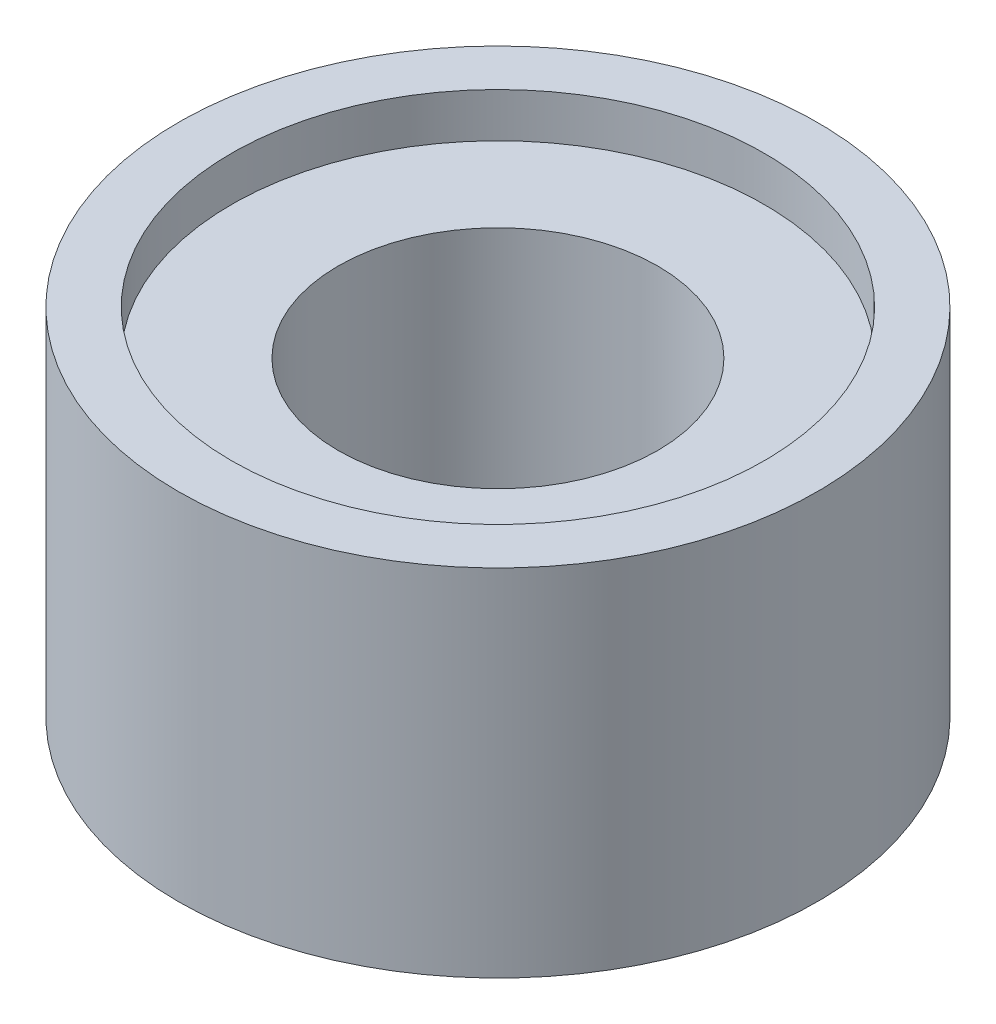
SolidWorks part; units mm, degrees
ref_plane "Front Plane" through (0, 0, 0) normal (0, 0, 1) x (1, 0, 0)
ref_plane "Top Plane" through (0, 0, 0) normal (0, 1, 0) x (1, 0, 0)
ref_plane "Right Plane" through (0, 0, 0) normal (1, 0, 0) x (0, 0, -1)
sketch "Sketch1" plane through (0, 0, 0) normal (0, 1, 0) x (1, 0, 0)
  circle A0 centre (0, 0) radius 9
  circle A1 centre (0, 0) radius 15
  dimension "D1" = 18
  dimension "D2" = 30
extrude "Boss-Extrude1" add sketch "Sketch1" along normal mid plane 15
sketch "Sketch3" plane through (0, 0, 0) normal (0, 1, 0) x (1, 0, 0)
  circle A0 centre (0, 0) radius 15
  circle A1 centre (0, 0) radius 18
  dimension "D1" = 3
extrude "Boss-Extrude2" add sketch "Sketch3" along normal mid plane 20
